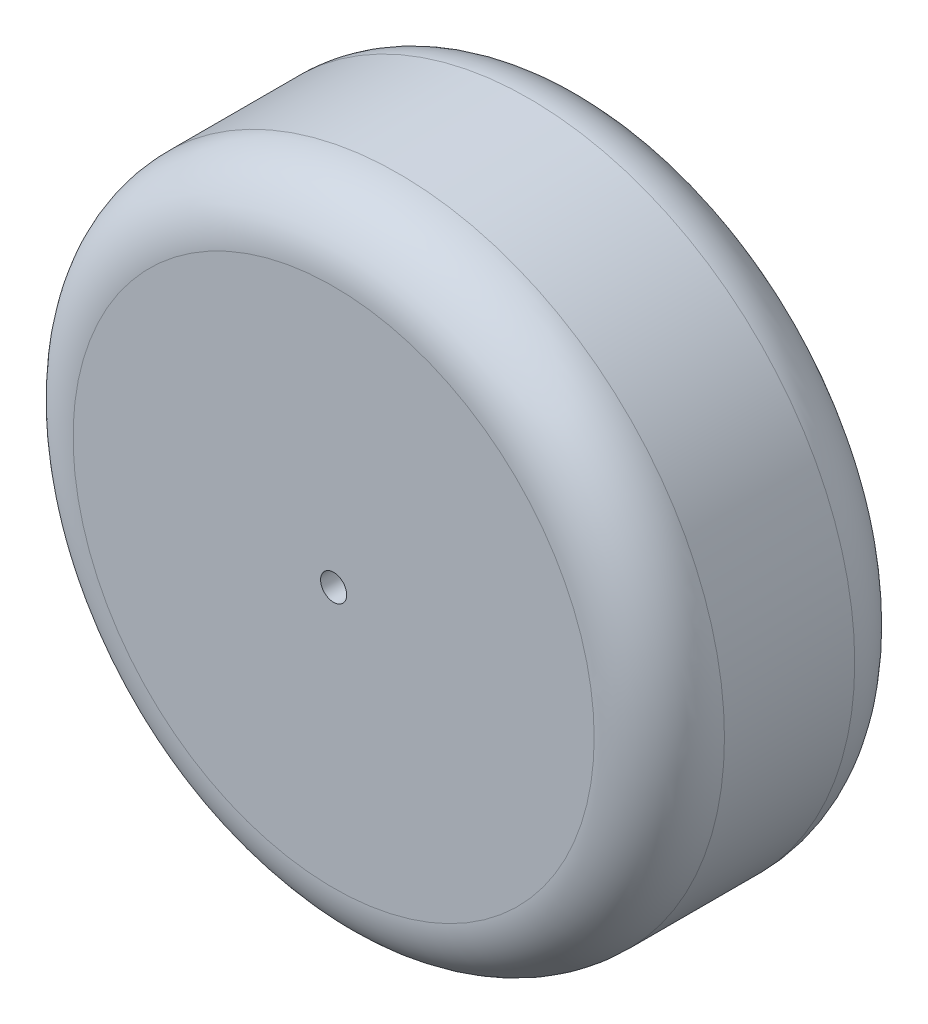
SolidWorks part; units mm, degrees
ref_plane "Front Plane" through (0, 0, 0) normal (0, 0, 1) x (1, 0, 0)
ref_plane "Top Plane" through (0, 0, 0) normal (0, 1, 0) x (1, 0, 0)
ref_plane "Right Plane" through (0, 0, 0) normal (1, 0, 0) x (0, 0, -1)
sketch "Sketch1" plane through (0, 0, 0) normal (0, 0, 1) x (1, 0, 0)
  circle A0 centre (0, 0) radius 25
  dimension "D1" = 50
extrude "Boss-Extrude1" add sketch "Sketch1" along normal blind 20
sketch "Sketch2" plane through (0, 0, 20) normal (0, 0, 1) x (1, 0, 0)
  circle A0 centre (0, 0) radius 1
  dimension "D1" = 2
extrude "Cut-Extrude1" cut sketch "Sketch2" against normal blind 6
fillet "Fillet1" radius 5 2 edges at (25, 0, 0) (25, 0, 20)
